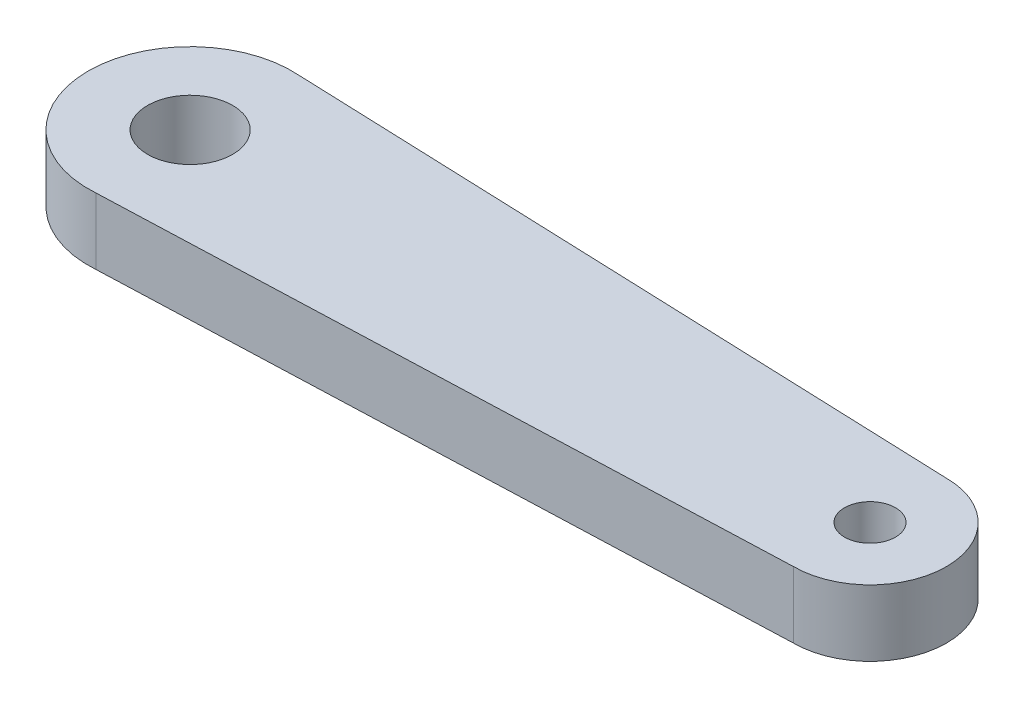
SolidWorks part; units mm, degrees
ref_plane "Front Plane" through (0, 0, 0) normal (0, 0, 1) x (1, 0, 0)
ref_plane "Top Plane" through (0, 0, 0) normal (0, 1, 0) x (1, 0, 0)
ref_plane "Right Plane" through (0, 0, 0) normal (1, 0, 0) x (0, 0, -1)
sketch "Sketch1" plane through (0, 0, 0) normal (0, 1, 0) x (1, 0, 0)
  line L0 (0.4494, 5.9831) -> (40, 4.5)
  line L1 (0.4494, -5.9831) -> (40, -4.5)
  arc A0 (0.4494, 5.9831) -> (0.4494, -5.9831) centre (0, 0) ccw
  arc A1 (40, -4.5) -> (40, 4.5) centre (40, 0) ccw
  dimension "D2" = 6
  dimension "D3" = 4.5
  dimension "D1" = 40
extrude "Boss-Extrude1" add sketch "Sketch1" along normal blind 3.9 contours L1 A1 L0 A0
sketch "Sketch2" plane through (0, 3.9, 0) normal (0, 1, 0) x (1, 0, 0)
  circle A0 centre (0, 0) radius 2.5
  circle A1 centre (40, 0) radius 1.5
  dimension "D1" = 5
  dimension "D2" = 3
extrude "Cut-Extrude1" cut sketch "Sketch2" against normal blind 10.5 and the other way blind 16
